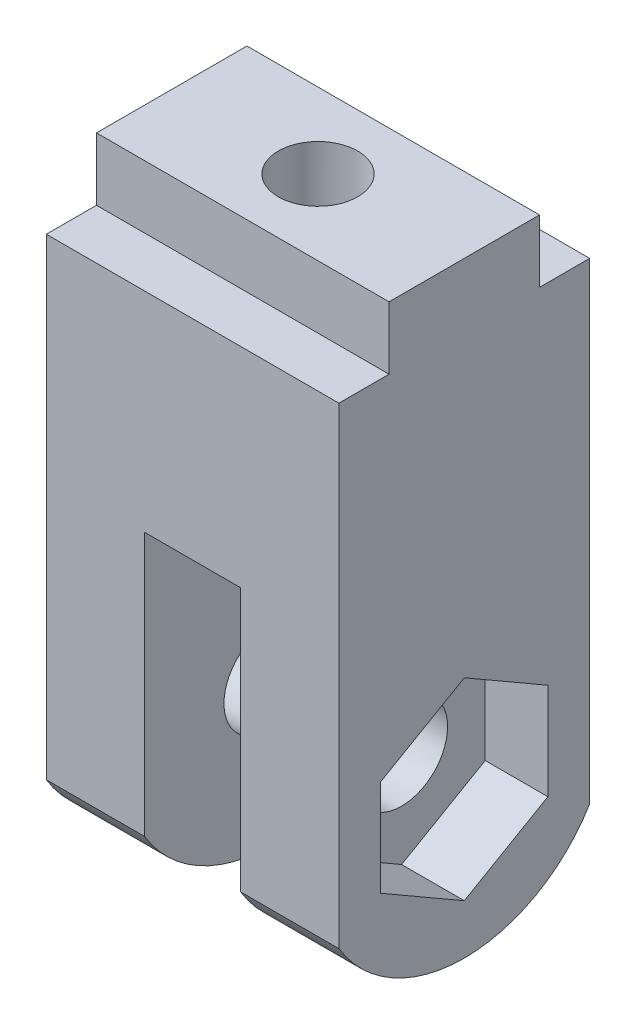
SolidWorks part; units mm, degrees
ref_plane "Front Plane" through (0, 0, 0) normal (0, 0, 1) x (1, 0, 0)
ref_plane "Top Plane" through (0, 0, 0) normal (0, 1, 0) x (1, 0, 0)
ref_plane "Right Plane" through (0, 0, 0) normal (1, 0, 0) x (0, 0, -1)
sketch "Sketch1" plane through (0, 0, 0) normal (0, 0, 1) x (1, 0, 0)
  line L0 (-1.15, 13) -> (-1.15, 21)
  line L1 (-1.15, 21) -> (1.15, 21)
  line L2 (1.15, 21) -> (1.15, 13)
  line L3 (1.15, 13) -> (3.5, 13)
  line L4 (3.5, 13) -> (3.5, 26)
  line L5 (3.5, 26) -> (-3.5, 26)
  line L6 (-3.5, 26) -> (-3.5, 13)
  line L7 (-3.5, 13) -> (-1.15, 13)
  line L8 (0, 21) -> (0, 0) construction
  line L9 (1, 20.5) -> (-1, 20.5) construction
  line L10 (3.5, 12.5) -> (1, 12.5) construction
  line L11 (-3.5, 12.5) -> (-3.5, -10.5) construction
  line L14 (-1, 19.1458) -> (-1, 12.5) construction
  dimension "D1" = 0.5
  dimension "D2" = 0.5
  dimension "D3" = 5
  dimension "D4" = 0.15
extrude "Boss-Extrude1" add sketch "Sketch1" against normal up to surface (6 mm away)
sketch "Sketch2" plane through (3.5, 0, 0) normal (1, 0, 0) x (0, 0, -1)
  line L0 (0, 13) -> (0, 26) construction
  line L1 (6, 26) -> (6, 13) construction
  line L2 (6, 13) -> (0, 13) construction
  line L3 (0, 18.3028) -> (0, 13)
  line L4 (0, 13) -> (6, 13)
  line L5 (6, 13) -> (6, 14.6972)
  circle A0 centre (3, 16.5) radius 1.1 construction
  circle A1 centre (3, 16.5) radius 1.1
  arc A2 (0, 18.3028) -> (6, 14.6972) centre (3, 16.5) ccw
  line M1 (6, 13) -> (6, 26)
  line M3 (0, 26) -> (0, 13)
  line M4 (0, 13) -> (6, 13)
extrude "Cut-Extrude1" cut sketch "Sketch2" against normal through all contours A1 | A2 M3 M4 | A2 L4 M1
sketch "Sketch3" plane through (3.5, 0, 0) normal (1, 0, 0) x (0, 0, -1)
  line L1 (3, 18.8094) -> (1, 17.6547)
  line L2 (1, 17.6547) -> (1, 15.3453)
  line L3 (1, 15.3453) -> (3, 14.1906)
  line L4 (3, 14.1906) -> (5, 15.3453)
  line L5 (5, 15.3453) -> (5, 17.6547)
  line L6 (5, 17.6547) -> (3, 18.8094)
  circle A0 centre (3, 16.5) radius 2 construction
  dimension "D1" = 4
extrude "Cut-Extrude2" cut sketch "Sketch3" against normal blind 1.5
sketch "Sketch4" plane through (0, 26, 0) normal (0, 1, 0) x (1, 0, 0)
  line L0 (-3.5, 6) -> (3.5, 0) construction
  line L1 (3.5, 6) -> (3.5, 0) construction
  line L2 (-3.5, 1.2) -> (3.5, 1.2)
  line L3 (-3.5, 1.2) -> (-3.5, 4.8)
  line L4 (-3.5, 4.8) -> (3.5, 4.8)
  line L5 (3.5, 1.2) -> (3.5, 4.8)
  line L6 (-3.5, 1.2) -> (3.5, 4.8) construction
  line L7 (-3.5, 4.8) -> (3.5, 1.2) construction
  point P4 (0, 3)
  dimension "D1" = 3.6
extrude "Boss-Extrude2" add sketch "Sketch4" along normal blind 1.5
sketch "Sketch5" plane through (0, 27.5, 0) normal (0, 1, 0) x (1, 0, 0)
  line L0 (-3.5, 4.8) -> (3.5, 1.2) construction
  circle A0 centre (0, 3) radius 0.95
  dimension "D1" = 1.9
extrude "Cut-Extrude3" cut sketch "Sketch5" against normal up to surface (6.5 mm away) up to face at (0, 21, -3)
